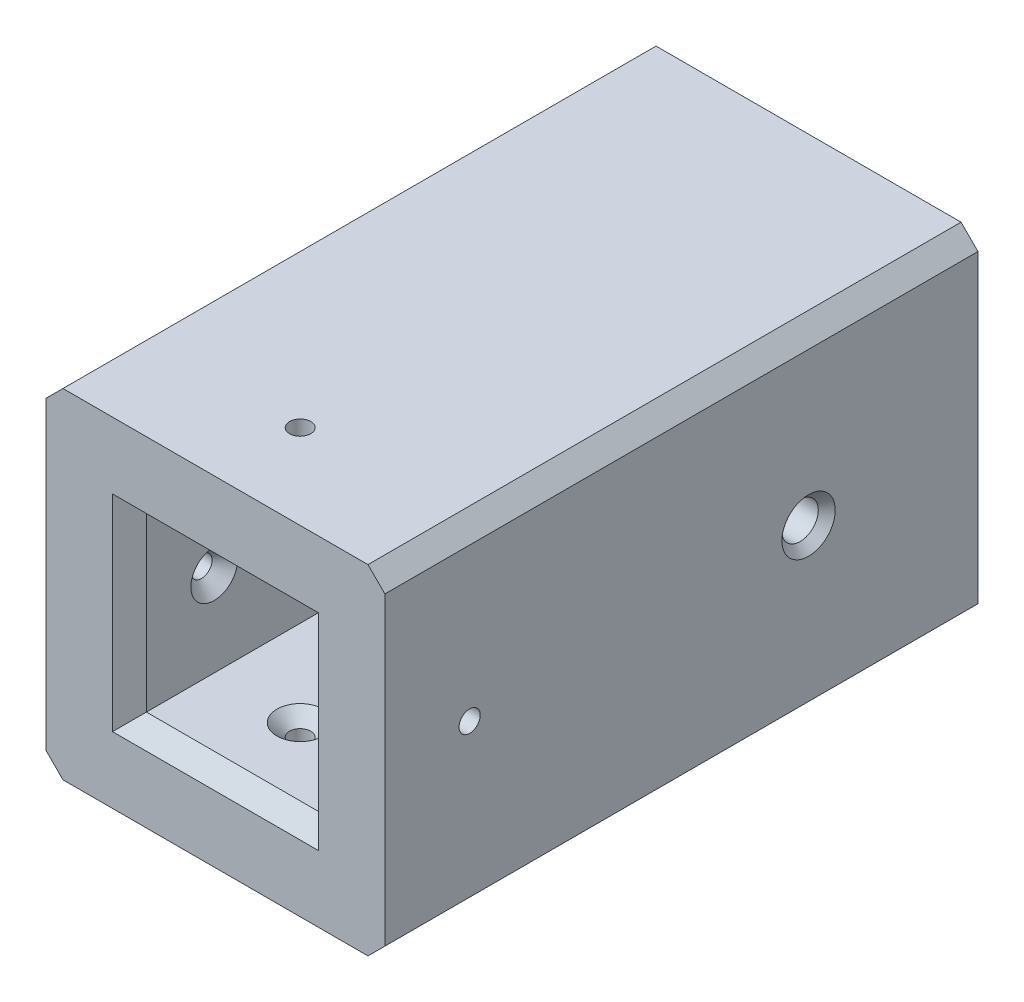
SolidWorks part; units mm, degrees
ref_plane "前视基准面" through (0, 0, 0) normal (0, 0, 1) x (1, 0, 0)
ref_plane "上视基准面" through (0, 0, 0) normal (0, 1, 0) x (1, 0, 0)
ref_plane "右视基准面" through (0, 0, 0) normal (1, 0, 0) x (0, 0, -1)
sketch "草图1" [suppressed] plane through (0, 0, 0) normal (0, 0, 1) x (1, 0, 0)
  circle A0 centre (0, 0) radius 53.418
sketch "草图2" plane through (0, 0, 0) normal (0, 0, 1) x (1, 0, 0)
  line L1 (0, 0) -> (40, 0)
  line L2 (0, 0) -> (0, 40)
  line L3 (0, 40) -> (40, 40)
  line L4 (40, 0) -> (40, 40)
  line L5 (9.85, 9.85) -> (30.15, 9.85)
  line L6 (9.85, 9.85) -> (9.85, 30.15)
  line L7 (9.85, 30.15) -> (30.15, 30.15)
  line L8 (30.15, 9.85) -> (30.15, 30.15)
  dimension "D1" = 40
  dimension "D2" = 40
  dimension "D3" = 20.3
  dimension "D4" = 20.3
  dimension "D5" = 9.85
  dimension "D6" = 9.85
extrude "凸台-拉伸1" add sketch "草图2" along normal blind 94
chamfer "倒角1" distance 2 angle 45 4 edges at (9.85, 20, 94) (20, 9.85, 94) (30.15, 20, 94) (20, 30.15, 94)
chamfer "倒角2" distance 2 angle 45 4 edges at (0, 0, 47) (0, 40, 47) (40, 40, 47) (40, 0, 47)
sketch "草图3" plane through (0, 0, 0) normal (0, 0, -1) x (-1, 0, 0)
  line L0 (0, 38) -> (0, 2) construction
  line L1 (-55, 55) -> (15, 55)
  line L2 (-55, 55) -> (-55, -15)
  line L3 (-55, -15) -> (15, -15)
  line L4 (15, 55) -> (15, -15)
  line L5 (-2, 0) -> (-38, 0) construction
  dimension "D1" = 70
  dimension "D2" = 70
  dimension "D3" = 15
  dimension "D4" = 15
extrude "凸台-拉伸2" [suppressed] add sketch "草图3" against normal blind 10
sketch "草图4" [suppressed] plane through (0, 0, 10) normal (0, 0, 1) x (1, 0, 0)
  line L0 (-3.5, 49) -> (-1.5, 49) construction
  line L1 (-3.5, 50.7) -> (-1.5, 50.7)
  line L2 (-3.5, 47.3) -> (-1.5, 47.3)
  line L3 (41.5, 49) -> (43.5, 49) construction
  line L4 (41.5, 50.7) -> (43.5, 50.7)
  line L5 (41.5, 47.3) -> (43.5, 47.3)
  line L6 (-15, 20) -> (55, 20) construction
  line L12 (-15, 55) -> (55, 55) construction
  line L17 (41.5, -9) -> (43.5, -9) construction
  line L18 (41.5, -10.7) -> (43.5, -10.7)
  line L19 (41.5, -7.3) -> (43.5, -7.3)
  line L20 (-3.5, -9) -> (-1.5, -9) construction
  line L21 (-3.5, -10.7) -> (-1.5, -10.7)
  line L22 (-3.5, -7.3) -> (-1.5, -7.3)
  arc A0 (-3.5, 50.7) -> (-3.5, 47.3) centre (-3.5, 49) ccw
  arc A1 (-1.5, 47.3) -> (-1.5, 50.7) centre (-1.5, 49) ccw
  arc A2 (41.5, 50.7) -> (41.5, 47.3) centre (41.5, 49) ccw
  arc A3 (43.5, 47.3) -> (43.5, 50.7) centre (43.5, 49) ccw
  arc A8 (41.5, -10.7) -> (41.5, -7.3) centre (41.5, -9) cw
  arc A9 (43.5, -7.3) -> (43.5, -10.7) centre (43.5, -9) cw
  arc A10 (-3.5, -10.7) -> (-3.5, -7.3) centre (-3.5, -9) cw
  arc A11 (-1.5, -7.3) -> (-1.5, -10.7) centre (-1.5, -9) cw
  point P2 (-2.5, 49)
  point P7 (42.5, 49)
  point P17 (42.5, -9)
  point P25 (-2.5, -9)
  point P29 (20, 55)
  dimension "D1" = 1.7
  dimension "D2" = 1.7
  dimension "D3" = 2
  dimension "D4" = 2
  dimension "D5" = 45
  dimension "D6" = 22.5
  dimension "D7" = 6
extrude "切除-拉伸1" [suppressed] cut sketch "草图4" against normal blind 10
chamfer "倒角3" [suppressed] distance 5 angle 45
chamfer "倒角4" [suppressed] distance 5 angle 45
sketch "草图5" plane through (0, 0, 0) normal (0, -1, 0) x (1, 0, 0)
  line L0 (2, 94) -> (38, 94) construction
  circle A0 centre (20, 84) radius 1.25
  dimension "D1" = 2.5
  dimension "D2" = 10
extrude "切除-拉伸2" cut sketch "草图5" against normal blind 48
sketch "草图6" plane through (0, 40, 0) normal (0, 1, 0) x (1, 0, 0)
  line L1 (9.85, -33.7) -> (30.15, -33.7)
  line L2 (9.85, -33.7) -> (9.85, -54)
  line L3 (9.85, -54) -> (30.15, -54)
  line L4 (30.15, -33.7) -> (30.15, -54)
  line L5 (30.15, -92) -> (30.15, 0) construction
  line L6 (38, -94) -> (2, -94) construction
  dimension "D1" = 20.3
  dimension "D2" = 20.3
  dimension "D3" = 0
  dimension "D4" = 40
extrude "切除-拉伸3" [suppressed] cut sketch "草图6" against normal blind 79
sketch "草图7" plane through (40, 0, 0) normal (1, 0, 0) x (0, 0, -1)
  line L0 (-94, 2) -> (-94, 38) construction
  circle A0 centre (-44, 20) radius 2.15
  dimension "D1" = 4.3
  dimension "D2" = 50
extrude "切除-拉伸4" cut sketch "草图7" against normal blind 79
chamfer "倒角5" [suppressed] distance 2 angle 45
chamfer "倒角6" distance 1 angle 45 2 edges at (0, 20, 41.85) (40, 20, 41.85)
sketch "草图8" plane through (0, 0, 0) normal (0, 0, -1) x (-1, 0, 0)
  line L1 (-51.4366, 44.2175) -> (14.4584, 44.2175)
  line L2 (-51.4366, 44.2175) -> (-51.4366, -9.9256)
  line L3 (-51.4366, -9.9256) -> (14.4584, -9.9256)
  line L4 (14.4584, 44.2175) -> (14.4584, -9.9256)
extrude "切除-拉伸5" cut sketch "草图8" against normal blind 24
sketch "草图9" plane through (0, 0, 0) normal (-1, 0, 0) x (0, 0, 1)
  line L0 (84, 40) -> (84, 30.15) construction
  line L2 (94, 38) -> (94, 2) construction
  line L3 (24, 40) -> (94, 40) construction
  circle A0 centre (84, 20) radius 1.25
  dimension "D1" = 2.5
  dimension "D2" = 10
  dimension "D3" = 20
extrude "切除-拉伸6" cut sketch "草图9" against normal blind 49
chamfer "倒角7" distance 1.5 angle 45 4 edges at (20, 9.85, 85.25) (9.85, 20, 82.75) (20, 30.15, 82.75) (30.15, 20, 85.25)
chamfer "倒角8" distance 2 angle 45 4 edges at (9.85, 20, 24) (20, 30.15, 24) (30.15, 20, 24) (20, 9.85, 24)
